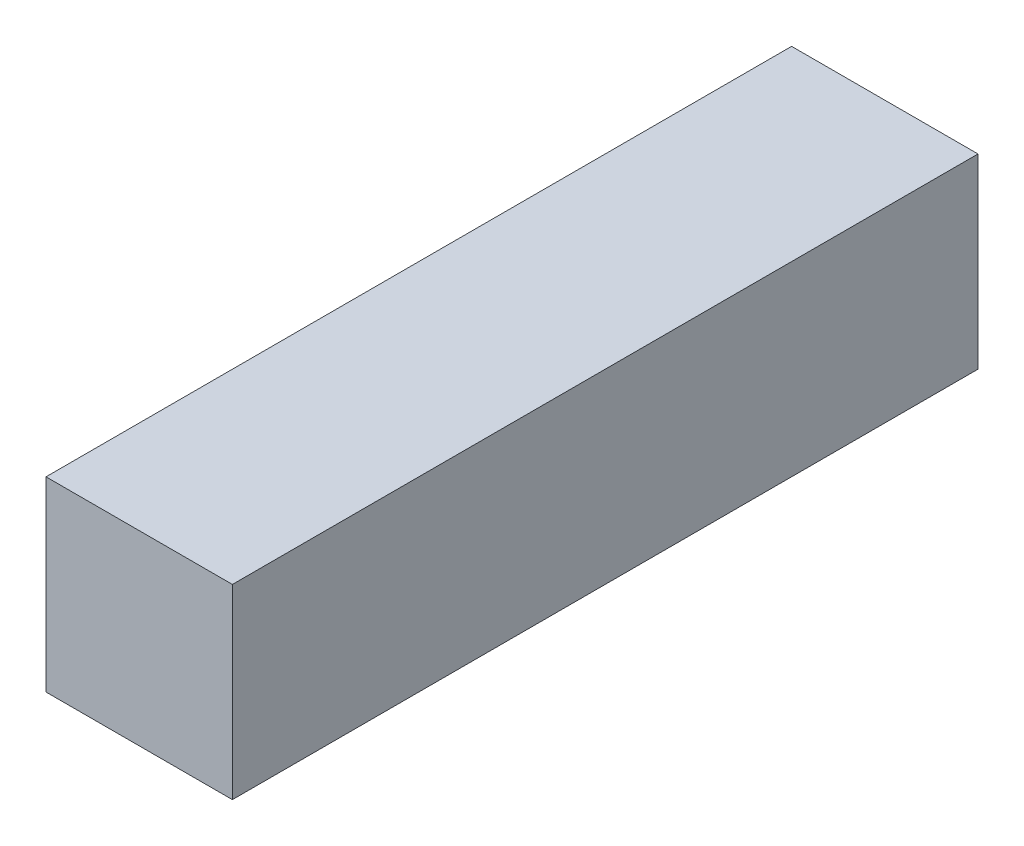
SolidWorks part; units mm, degrees
ref_plane "Front Plane" through (0, 0, 0) normal (0, 0, 1) x (1, 0, 0)
ref_plane "Top Plane" through (0, 0, 0) normal (0, 1, 0) x (1, 0, 0)
ref_plane "Right Plane" through (0, 0, 0) normal (1, 0, 0) x (0, 0, -1)
sketch "Sketch1" plane through (0, 0, 0) normal (0, 0, 1) x (1, 0, 0)
  line L4 (-4.75, 1.25) -> (-4.75, -1.75)
  line L5 (-4.75, 1.25) -> (-4.75, -1.75)
  line L6 (-4.75, -1.75) -> (-1.75, -1.75)
  line L7 (-4.75, -1.75) -> (-1.75, -1.75)
  line L8 (-1.75, -1.75) -> (-1.75, 1.25)
  line L9 (-1.75, -1.75) -> (-1.75, 1.25)
  line L10 (-1.75, 1.25) -> (-4.75, 1.25)
  line L11 (-1.75, 1.25) -> (-4.75, 1.25)
  dimension "D1" = 0
extrude "Boss-Extrude1" add sketch "Sketch1" along normal blind 12
